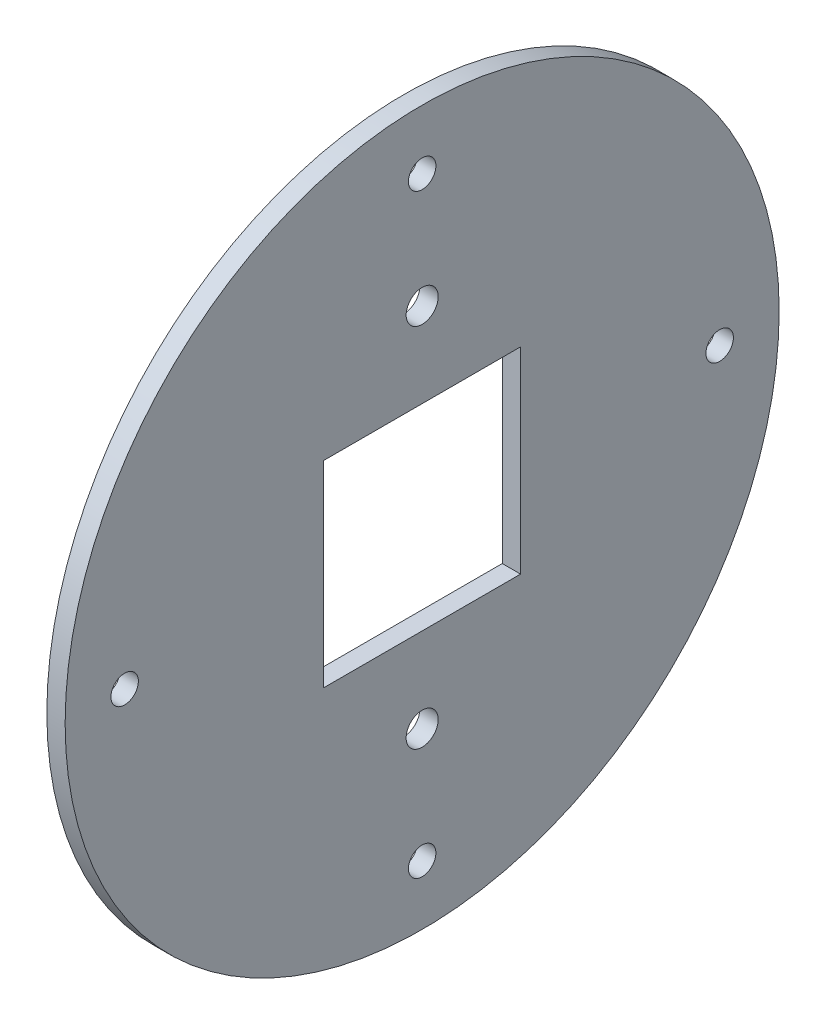
SolidWorks part; units mm, degrees
material "1060 合金"
ref_plane "前视基准面" through (0, 0, 0) normal (0, 0, 1) x (1, 0, 0)
ref_plane "上视基准面" through (0, 0, 0) normal (0, 1, 0) x (1, 0, 0)
ref_plane "右视基准面" through (0, 0, 0) normal (1, 0, 0) x (0, 0, -1)
sketch "草图1" plane through (0, 0, 0) normal (1, 0, 0) x (0, 0, -1)
  circle A0 centre (0, 0) radius 156
extrude "凸台-拉伸1" add sketch "草图1" along normal blind 8
sketch "草图5" plane through (8, 0, 0) normal (1, 0, 0) x (0, 0, -1)
  circle A0 centre (0, 130) radius 6
extrude "切除-拉伸4" cut sketch "草图5" against normal blind 10
pattern_circular "阵列(圆周)3" count 4 over 360 about axis through (0, 0, 0) along (1, 0, 0) of "切除-拉伸4"
sketch "草图6" plane through (8, 0, 0) normal (1, 0, 0) x (0, 0, -1)
  line L1 (-43, -43) -> (43, -43)
  line L2 (-43, -43) -> (-43, 43)
  line L3 (-43, 43) -> (43, 43)
  line L4 (43, -43) -> (43, 43)
  line L5 (-43, -43) -> (43, 43) construction
  line L6 (-43, 43) -> (43, -43) construction
  point P0 (0, 0)
  dimension "D1" = 86
  dimension "D2" = 86
extrude "切除-拉伸5" cut sketch "草图6" against normal blind 10
sketch "草图7" plane through (8, 0, 0) normal (1, 0, 0) x (0, 0, -1)
  circle A0 centre (0, 80) radius 7
  circle A1 centre (0, -80) radius 7
extrude "切除-拉伸6" cut sketch "草图7" against normal blind 10
